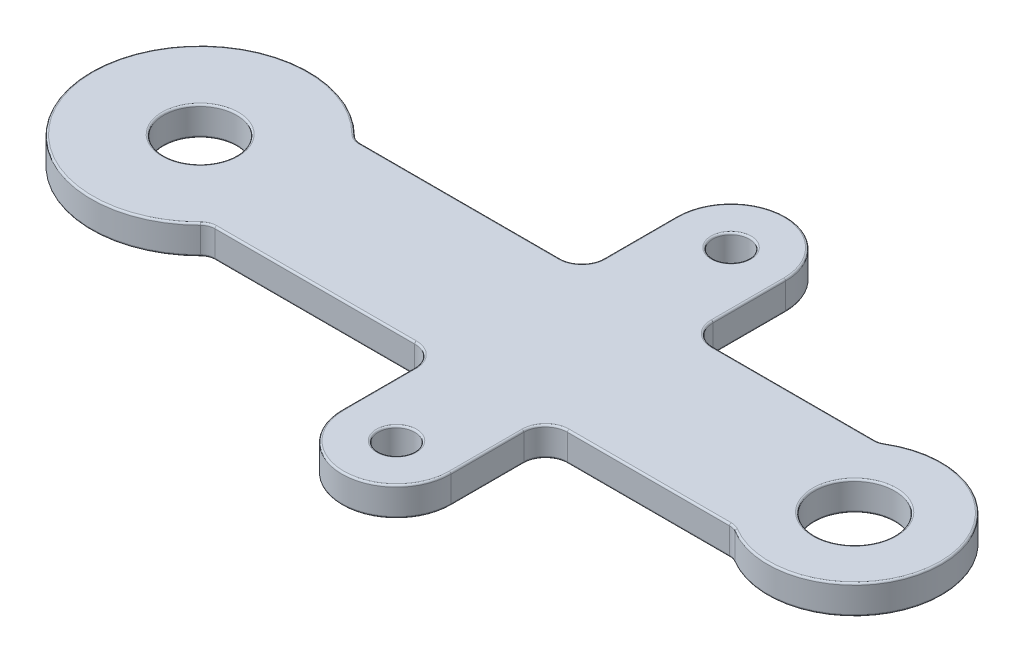
SolidWorks part; units mm, degrees
ref_plane "前视基准面" through (0, 0, 0) normal (0, 0, 1) x (1, 0, 0)
ref_plane "上视基准面" through (0, 0, 0) normal (0, 1, 0) x (1, 0, 0)
ref_plane "右视基准面" through (0, 0, 0) normal (1, 0, 0) x (0, 0, -1)
sketch "草图1" plane through (0, 0, 0) normal (0, 1, 0) x (1, 0, 0)
  line L0 (-79.8254, 0) -> (43.5663, 0) construction
  line L1 (0, 81.5805) -> (0, -29.6577) construction
  line L2 (22.3563, 20.0049) -> (85, 20.0049)
  line L3 (22.3563, -20.0049) -> (85, -20.0049)
  line L4 (115, 20.0049) -> (166.7409, 20.0049)
  line L5 (115, -20.0049) -> (166.7409, -20.0049)
  line L7 (85, 46) -> (85, 20.0049)
  line L8 (115, 46) -> (115, 20.0049)
  line L9 (115, -46) -> (115, -20.0049)
  line L10 (85, -46) -> (85, -20.0049)
  circle A0 centre (0, 0) radius 10
  arc A1 (22.3563, 20.0049) -> (22.3563, -20.0049) centre (0, 0) ccw
  circle A2 centre (100, 46) radius 5
  circle A3 centre (180, 0) radius 11
  arc A4 (166.7409, -20.0049) -> (166.7409, 20.0049) centre (180, 0) ccw
  circle A5 centre (100, -46) radius 5
  arc A8 (115, 46) -> (85, 46) centre (100, 46) ccw
  arc A9 (115, -46) -> (85, -46) centre (100, -46) cw
  point P9 (180, 0)
  point P13 (22.3563, 20.0049)
  point P24 (100, 0)
  point P29 (85, 46)
  point P30 (115, 46)
extrude "凸台-拉伸1" add sketch "草图1" along normal blind 8
fillet "圆角1" radius 6 1 edges at (85, 4, -20.0049)
fillet "圆角2" radius 6 1 edges at (115, 4, -20.0049)
fillet "圆角3" radius 6 1 edges at (115, 4, 20.0049)
fillet "圆角4" radius 6 1 edges at (85, 4, 20.0049)
fillet "圆角5" radius 4 1 edges at (22.3563, 4, -20.0049)
fillet "圆角6" radius 4 1 edges at (22.3563, 4, 20.0049)
fillet "圆角7" radius 4 1 edges at (166.7409, 4, 20.0049)
fillet "圆角8" radius 4 1 edges at (166.7409, 4, -20.0049)
fillet "圆角9" radius 0.5 48 edges at (180, 8, 11) (100, 8, -41) (0, 8, 10) (100, 8, 41) (204, 8, 0) (166.6543, 8, 20.1502) (143.293, 8, 20.0049) (116.7574, 8, 21.7622) (115, 8, 36.0024) (100, 8, 61) (85, 8, 36.0024) (83.2426, 8, 21.7622) (51.5392, 8, 20.0049) (22.5448, 8, 20.3105) (-30, 8, 0) (22.5448, 8, -20.3105) (51.5392, 8, -20.0049) (83.2426, 8, -21.7622) (85, 8, -36.0024) (100, 8, -61) (115, 8, -36.0024) (116.7574, 8, -21.7622) (143.293, 8, -20.0049) (166.6543, 8, -20.1502) (180, 0, 11) (100, 0, 41) (100, 0, -41) (0, 0, 10) (22.5448, 0, 20.3105) (51.5392, 0, 20.0049) (83.2426, 0, 21.7622) (85, 0, 36.0024) (100, 0, 61) (115, 0, 36.0024) (116.7574, 0, 21.7622) (143.293, 0, 20.0049) (166.6543, 0, 20.1502) (204, 0, 0) (166.6543, 0, -20.1502) (143.293, 0, -20.0049) (116.7574, 0, -21.7622) (115, 0, -36.0024) (100, 0, -61) (85, 0, -36.0024) (83.2426, 0, -21.7622) (51.5392, 0, -20.0049) (22.5448, 0, -20.3105) (-30, 0, 0)
